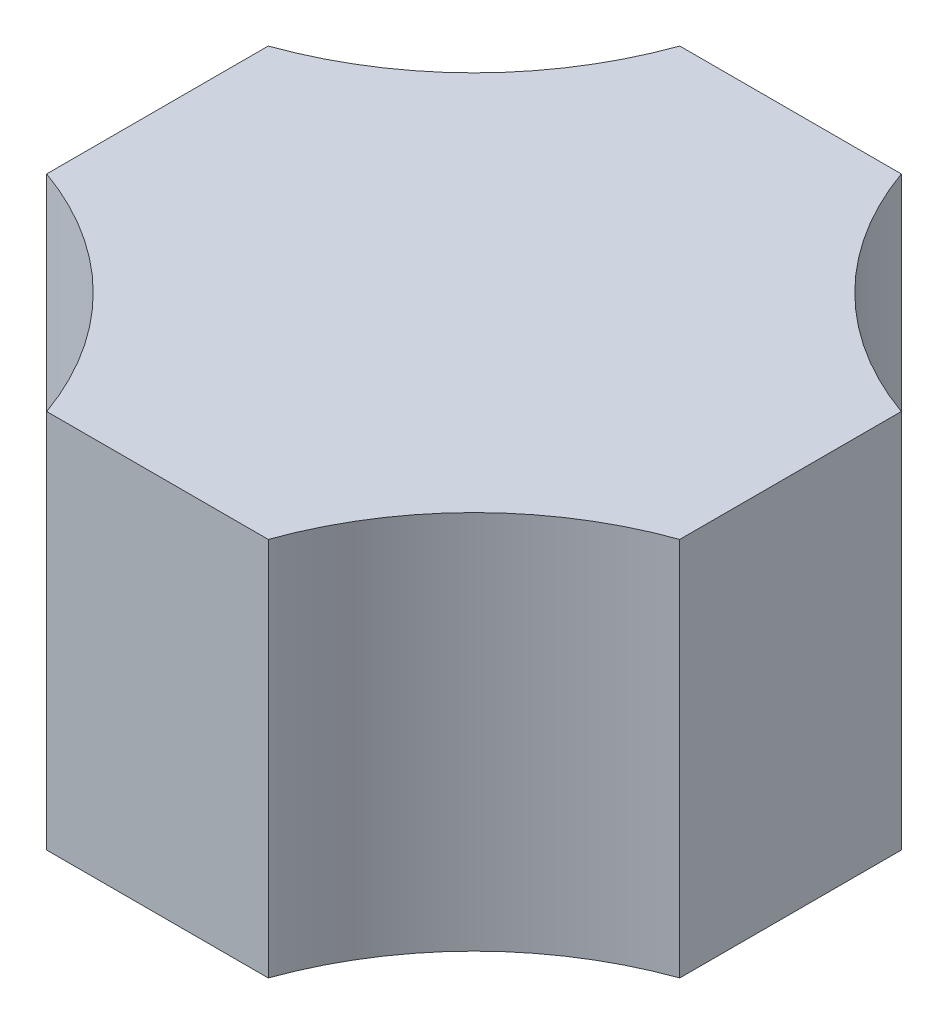
SolidWorks part; units mm, degrees
ref_plane "Front Plane" through (0, 0, 0) normal (0, 0, 1) x (1, 0, 0)
ref_plane "Top Plane" through (0, 0, 0) normal (0, 1, 0) x (1, 0, 0)
ref_plane "Right Plane" through (0, 0, 0) normal (1, 0, 0) x (0, 0, -1)
sketch "Sketch2" plane through (0, 0, 0) normal (0, 1, 0) x (1, 0, 0)
  line L0 (25.4, 12.7) -> (0, 12.7) construction
  line L1 (8.255, 25.4) -> (17.145, 25.4)
  line L2 (25.4, 17.145) -> (25.4, 8.255)
  line L3 (25.4, 8.255) -> (25.4726, 8.245)
  line L4 (17.145, 0) -> (8.255, 0)
  line L5 (12.7, 0) -> (12.7, 25.4) construction
  line L6 (0, 8.255) -> (0, 17.145)
  line L8 (0, 12.7) -> (-39.1806, -25.7699) construction
  arc A0 (17.145, 25.4) -> (25.4, 17.145) centre (29.9332, 29.9332) ccw
  arc A1 (17.145, 0) -> (25.4, 8.255) centre (29.9332, -4.5332) cw
  arc A2 (8.255, 0) -> (0, 8.255) centre (-4.5332, -4.5332) ccw
  arc A3 (8.255, 25.4) -> (0, 17.145) centre (-4.5332, 29.9332) cw
extrude "Boss-Extrude6" add sketch "Sketch2" against normal blind 15.24 contours L1 A3 L6 A2 L4 A1 L2 A0
ref_plane "Plane4" through (0, 0, -12.7) normal (0, 0, 1) x (1, 0, 0)
sketch "Sketch12" plane through (0, 0, -12.7) normal (0, 0, 1) x (1, 0, 0)
  line L0 (12.6011, 0) -> (12.6011, 12.7) construction
  dimension "D1" = 12.7
sketch "Sketch13" plane through (0, 0, -12.7) normal (0, 0, 1) x (1, 0, 0)
  line L0 (12.6011, 0) -> (17.4492, 12.398) construction
